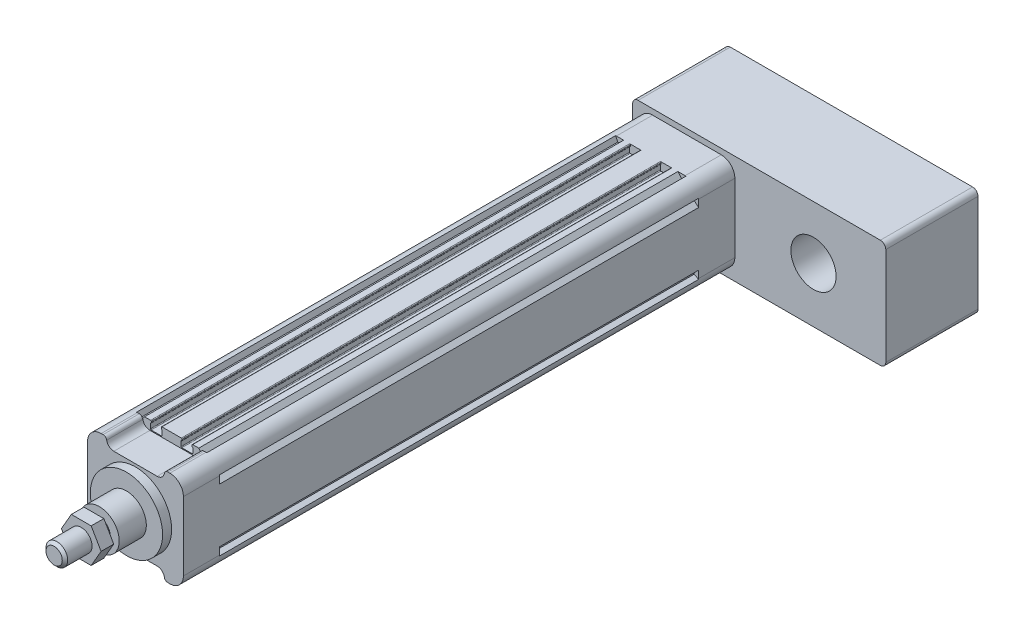
SolidWorks part; units mm, degrees
ref_plane "Front" through (0, 0, 0) normal (0, 0, 1) x (1, 0, 0)
ref_plane "Top" through (0, 0, 0) normal (0, 1, 0) x (1, 0, 0)
ref_plane "Right" through (0, 0, 0) normal (1, 0, 0) x (0, 0, -1)
sketch "草图1" plane through (0, 0, 0) normal (0, 0, 1) x (1, 0, 0)
  line L0 (19.7737, 3) -> (23.3, 3)
  line L1 (23.3, 3) -> (23.3, -3)
  line L2 (23.3, -3) -> (19.7737, -3)
  line L3 (-19.7737, -3) -> (-23.3, -3)
  line L4 (-23.3, -3) -> (-23.3, 3)
  line L5 (-23.3, 3) -> (-19.7737, 3)
  line L6 (-18.2, 24) -> (-19.4434, 26.4869)
  line L7 (-26.4869, 19.4434) -> (-24, 18.2)
  line L8 (-24, 18.2) -> (-24, 17.1)
  line L9 (-24, 17.1) -> (-26.5, 15)
  line L10 (-26.5, 15) -> (-26.5, -15)
  line L11 (-26.5, -15) -> (-24, -17.1)
  line L12 (-24, -17.1) -> (-24, -18.2)
  line L13 (-24, -18.2) -> (-26.4869, -19.4434)
  line L14 (-19.4434, -26.4869) -> (-18.2, -24)
  line L15 (-18.2, -24) -> (-17.1, -24)
  line L16 (-17.1, -24) -> (-15, -26.5)
  line L17 (-15, -26.5) -> (-11.65, -26.5)
  line L18 (-11.25, -26.1) -> (-11.25, -25.6)
  line L19 (-11.65, -25.2) -> (-11.75, -25.2)
  line L20 (-11.75, -25.2) -> (-11.75, -22.4)
  line L21 (-11.35, -22) -> (-5.65, -22)
  line L22 (-5.25, -22.4) -> (-5.25, -25.2)
  line L23 (-5.25, -25.2) -> (-5.35, -25.2)
  line L24 (-5.75, -25.6) -> (-5.75, -26.1)
  line L25 (-5.35, -26.5) -> (5.35, -26.5)
  line L26 (5.75, -26.1) -> (5.75, -25.6)
  line L27 (5.35, -25.2) -> (5.25, -25.2)
  line L28 (5.25, -25.2) -> (5.25, -22.4)
  line L29 (5.65, -22) -> (11.35, -22)
  line L30 (11.75, -22.4) -> (11.75, -25.2)
  line L31 (11.75, -25.2) -> (11.65, -25.2)
  line L32 (11.25, -25.6) -> (11.25, -26.1)
  line L33 (11.65, -26.5) -> (15, -26.5)
  line L34 (15, -26.5) -> (17.1, -24)
  line L35 (17.1, -24) -> (18.2, -24)
  line L36 (18.2, -24) -> (19.4434, -26.4869)
  line L37 (26.4869, -19.4434) -> (24, -18.2)
  line L38 (24, -18.2) -> (24, -17.1)
  line L39 (24, -17.1) -> (26.5, -15)
  line L40 (26.5, -15) -> (26.5, 15)
  line L41 (26.5, 15) -> (24, 17.1)
  line L42 (24, 17.1) -> (24, 18.2)
  line L43 (24, 18.2) -> (26.4869, 19.4434)
  line L44 (19.4434, 26.4869) -> (18.2, 24)
  line L45 (18.2, 24) -> (17.1, 24)
  line L46 (17.1, 24) -> (15, 26.5)
  line L47 (15, 26.5) -> (11.65, 26.5)
  line L48 (11.25, 26.1) -> (11.25, 25.6)
  line L49 (11.65, 25.2) -> (11.75, 25.2)
  line L50 (11.75, 25.2) -> (11.75, 22.4)
  line L51 (11.35, 22) -> (5.65, 22)
  line L52 (5.25, 22.4) -> (5.25, 25.2)
  line L53 (5.25, 25.2) -> (5.35, 25.2)
  line L54 (5.75, 25.6) -> (5.75, 26.1)
  line L55 (5.35, 26.5) -> (-5.35, 26.5)
  line L56 (-5.75, 26.1) -> (-5.75, 25.6)
  line L57 (-5.35, 25.2) -> (-5.25, 25.2)
  line L58 (-5.25, 25.2) -> (-5.25, 22.4)
  line L59 (-5.65, 22) -> (-11.35, 22)
  line L60 (-11.75, 22.4) -> (-11.75, 25.2)
  line L61 (-11.75, 25.2) -> (-11.65, 25.2)
  line L62 (-11.25, 25.6) -> (-11.25, 26.1)
  line L63 (-11.65, 26.5) -> (-15, 26.5)
  line L64 (-15, 26.5) -> (-17.1, 24)
  line L65 (-17.1, 24) -> (-18.2, 24)
  arc A0 (19.7737, 3) -> (-19.7737, 3) centre (0, 0) ccw
  arc A1 (-19.7737, -3) -> (19.7737, -3) centre (0, 0) ccw
  circle A2 centre (19, 19) radius 2.1
  circle A3 centre (19, -19) radius 2.1
  circle A4 centre (-19, -19) radius 2.1
  circle A5 centre (-19, 19) radius 2.1
  arc A6 (-19.4434, 26.4869) -> (-26.4869, 19.4434) centre (-19, 19) ccw
  arc A7 (-26.4869, -19.4434) -> (-19.4434, -26.4869) centre (-19, -19) ccw
  arc A8 (-11.65, -26.5) -> (-11.25, -26.1) centre (-11.65, -26.1) ccw
  arc A9 (-11.25, -25.6) -> (-11.65, -25.2) centre (-11.65, -25.6) ccw
  arc A10 (-11.35, -22) -> (-11.75, -22.4) centre (-11.35, -22.4) ccw
  arc A11 (-5.25, -22.4) -> (-5.65, -22) centre (-5.65, -22.4) ccw
  arc A12 (-5.35, -25.2) -> (-5.75, -25.6) centre (-5.35, -25.6) ccw
  arc A13 (-5.75, -26.1) -> (-5.35, -26.5) centre (-5.35, -26.1) ccw
  arc A14 (5.35, -26.5) -> (5.75, -26.1) centre (5.35, -26.1) ccw
  arc A15 (5.75, -25.6) -> (5.35, -25.2) centre (5.35, -25.6) ccw
  arc A16 (5.65, -22) -> (5.25, -22.4) centre (5.65, -22.4) ccw
  arc A17 (11.75, -22.4) -> (11.35, -22) centre (11.35, -22.4) ccw
  arc A18 (11.65, -25.2) -> (11.25, -25.6) centre (11.65, -25.6) ccw
  arc A19 (11.25, -26.1) -> (11.65, -26.5) centre (11.65, -26.1) ccw
  arc A20 (19.4434, -26.4869) -> (26.4869, -19.4434) centre (19, -19) ccw
  arc A21 (26.4869, 19.4434) -> (19.4434, 26.4869) centre (19, 19) ccw
  arc A22 (11.65, 26.5) -> (11.25, 26.1) centre (11.65, 26.1) ccw
  arc A23 (11.25, 25.6) -> (11.65, 25.2) centre (11.65, 25.6) ccw
  arc A24 (11.35, 22) -> (11.75, 22.4) centre (11.35, 22.4) ccw
  arc A25 (5.25, 22.4) -> (5.65, 22) centre (5.65, 22.4) ccw
  arc A26 (5.35, 25.2) -> (5.75, 25.6) centre (5.35, 25.6) ccw
  arc A27 (5.75, 26.1) -> (5.35, 26.5) centre (5.35, 26.1) ccw
  arc A28 (-5.35, 26.5) -> (-5.75, 26.1) centre (-5.35, 26.1) ccw
  arc A29 (-5.75, 25.6) -> (-5.35, 25.2) centre (-5.35, 25.6) ccw
  arc A30 (-5.65, 22) -> (-5.25, 22.4) centre (-5.65, 22.4) ccw
  arc A31 (-11.75, 22.4) -> (-11.35, 22) centre (-11.35, 22.4) ccw
  arc A32 (-11.65, 25.2) -> (-11.25, 25.6) centre (-11.65, 25.6) ccw
  arc A33 (-11.25, 26.1) -> (-11.65, 26.5) centre (-11.65, 26.1) ccw
extrude "凸台-拉伸1" add sketch "草图1" along normal blind 265
sketch "草图6" plane through (0, 0, 265) normal (0, 0, 1) x (1, 0, 0)
  line L0 (0, 0) -> (19, 0) construction
  line L2 (-26.5, -19) -> (-26.5, 19)
  line L3 (-19, 26.5) -> (-17.9161, 26.5)
  line L4 (26.5, -19) -> (26.5, 19)
  line L5 (-26.5, -26.5) -> (26.5, 26.5) construction
  line L6 (-26.5, 26.5) -> (26.5, -26.5) construction
  line L7 (-12, 21.5) -> (12, 21.5)
  line L9 (19, 26.5) -> (17.9161, 26.5)
  line L10 (19, -26.5) -> (17.9161, -26.5)
  line L11 (-12, -21.5) -> (12, -21.5)
  line L12 (-19, -26.5) -> (-17.9161, -26.5)
  arc A0 (12, 21.5) -> (15.9441, 24.8333) centre (12, 25.5) ccw
  arc A1 (-15.9441, 24.8333) -> (-12, 21.5) centre (-12, 25.5) ccw
  arc A2 (-15.9441, 24.8333) -> (-17.9161, 26.5) centre (-17.9161, 24.5) ccw
  arc A3 (15.9441, 24.8333) -> (17.9161, 26.5) centre (17.9161, 24.5) cw
  arc A4 (-26.5, -19) -> (-19, -26.5) centre (-19, -19) ccw
  arc A5 (19, -26.5) -> (26.5, -19) centre (19, -19) ccw
  arc A6 (26.5, 19) -> (19, 26.5) centre (19, 19) ccw
  arc A7 (-26.5, 19) -> (-19, 26.5) centre (-19, 19) cw
  arc A8 (15.9441, -24.8333) -> (17.9161, -26.5) centre (17.9161, -24.5) ccw
  arc A9 (12, -21.5) -> (15.9441, -24.8333) centre (12, -25.5) cw
  arc A10 (-15.9441, -24.8333) -> (-12, -21.5) centre (-12, -25.5) cw
  arc A11 (-15.9441, -24.8333) -> (-17.9161, -26.5) centre (-17.9161, -24.5) cw
  point P0 (0, 0)
  point P9 (0, 21.5)
  point P13 (20, 20.8461)
  point P16 (-12, 20.8461)
  dimension "D5" = 4
  dimension "D6" = 2
  dimension "D7" = 2
  dimension "D9" = 7.5
  dimension "D1" = 53
  dimension "D2" = 53
  dimension "D3" = 26.5
  dimension "D4" = 24
  dimension "D8" = 5
extrude "凸台-拉伸2" add sketch "草图6" along normal blind 20
sketch "草图7" plane through (0, 0, 285) normal (0, 0, 1) x (1, 0, 0)
  circle A0 centre (0, 0) radius 20
  dimension "D1" = 40
extrude "凸台-拉伸3" add sketch "草图7" along normal blind 5
sketch "草图9" plane through (0, 0, 290) normal (0, 0, 1) x (1, 0, 0)
  circle A0 centre (0, 0) radius 11
  dimension "D1" = 22
extrude "凸台-拉伸4" add sketch "草图9" along normal blind 15
sketch "草图10" plane through (0, 0, 305) normal (0, 0, 1) x (1, 0, 0)
  circle A0 centre (0, 0) radius 6
  dimension "D1" = 12
extrude "凸台-拉伸5" add sketch "草图10" along normal blind 25
sketch "草图11" plane through (0, 0, 0) normal (0, 0, -1) x (-1, 0, 0)
  line L1 (-19, -26.5) -> (19, -26.5)
  line L2 (-26.5, -19) -> (-26.5, 19)
  line L3 (-19, 26.5) -> (19, 26.5)
  line L4 (26.5, -19) -> (26.5, 19)
  line L5 (-26.5, -26.5) -> (26.5, 26.5) construction
  line L6 (-26.5, 26.5) -> (26.5, -26.5) construction
  arc A0 (-26.5, -19) -> (-19, -26.5) centre (-19, -19) ccw
  arc A1 (19, -26.5) -> (26.5, -19) centre (19, -19) ccw
  arc A2 (26.5, 19) -> (19, 26.5) centre (19, 19) ccw
  arc A3 (-26.5, 19) -> (-19, 26.5) centre (-19, 19) cw
  point P0 (0, 0)
  dimension "D3" = 7.5
  dimension "D1" = 53
  dimension "D2" = 53
extrude "凸台-拉伸6" add sketch "草图11" along normal blind 20
sketch "草图12" plane through (0, 0, -20) normal (0, 0, -1) x (-1, 0, 0)
  line L1 (-107, -30.4042) -> (27, -30.4042)
  line L2 (-110, -27.4042) -> (-110, 26.5958)
  line L3 (-107, 29.5958) -> (27, 29.5958)
  line L4 (30, -27.4042) -> (30, 26.5958)
  line L5 (-110, -30.4042) -> (30, 29.5958) construction
  line L6 (-110, 29.5958) -> (30, -30.4042) construction
  arc A0 (27, 29.5958) -> (30, 26.5958) centre (27, 26.5958) cw
  arc A1 (30, -27.4042) -> (27, -30.4042) centre (27, -27.4042) cw
  arc A2 (-110, -27.4042) -> (-107, -30.4042) centre (-107, -27.4042) ccw
  arc A3 (-110, 26.5958) -> (-107, 29.5958) centre (-107, 26.5958) cw
  point P0 (-40, -0.4042)
  dimension "D4" = 3
  dimension "D1" = 60
  dimension "D2" = 140
  dimension "D3" = 30
extrude "凸台-拉伸7" add sketch "草图12" along normal blind 51
sketch "草图13" plane through (0, 0, -20) normal (0, 0, 1) x (1, 0, 0)
  circle A0 centre (70, 0) radius 12.5
  dimension "D2" = 25
  dimension "D1" = 70
extrude "切除-拉伸2" cut sketch "草图13" against normal blind 30
hole_wizard "M6 螺纹孔1" positions "草图14" profile "草图15" tap size "M6" standard "GB"
sketch "草图14" plane through (0, 0, -71) normal (0, 0, -1) x (-1, 0, 0)
  line L0 (30, -27.4042) -> (30, 26.5958) construction
  point P0 (19, -19)
  dimension "D1" = 11
  dimension "D2" = 19
sketch "草图15" plane through (-19, -19, -71) normal (1, 0, 0) x (0, 1, 0)
  line L0 (0, 0) -> (0, 16.5022)
  line L1 (0, 16.5022) -> (2.5, 15)
  line L2 (2.5, 15) -> (2.5, 0)
  line L5 (2.5, 0) -> (0, 0)
  line L10 (0, 16.5022) -> (-2.5, 15) construction
  line L11 (0, -6.35) -> (0, 107.95) construction
  dimension "螺纹孔钻头直径" = 5
  dimension "螺纹孔钻头深度" = 15
  dimension "导头角度" = 118
cosmetic thread "孔螺蚊线4" parameters "D1"=12, "D2"=6
pattern_linear "阵列(线性)1" count 2 spacing 38 along (0, 1, 0) count 2 spacing 38 along (1, 0, 0) of "M6 螺纹孔1"
hole_wizard "M6 螺纹孔2" positions "草图16" profile "草图17" tap size "M6" standard "GB"
sketch "草图16" plane through (0, 0, -71) normal (0, 0, -1) x (-1, 0, 0)
  circle A1 centre (-19, 19) radius 2.5 construction
  circle A2 centre (-19, -19) radius 2.5 construction
  point P0 (-84, -19)
  point P2 (-84, 19)
  dimension "D3" = 65
  dimension "D1" = 19
  dimension "D2" = 19
  dimension "D4" = 65
sketch "草图17" plane through (84, -19, -71) normal (1, 0, 0) x (0, 1, 0)
  line L0 (0, 0) -> (0, 16.5022)
  line L1 (0, 16.5022) -> (2.5, 15)
  line L2 (2.5, 15) -> (2.5, 0)
  line L5 (2.5, 0) -> (0, 0)
  line L10 (0, 16.5022) -> (-2.5, 15) construction
  line L11 (0, -6.35) -> (0, 107.95) construction
  dimension "螺纹孔钻头直径" = 5
  dimension "螺纹孔钻头深度" = 15
  dimension "导头角度" = 118
cosmetic thread "孔螺蚊线5" parameters "D1"=12, "D2"=6
cosmetic thread "孔螺蚊线6" parameters "D1"=12, "D2"=6
hole_wizard "M6 螺纹孔3" positions "草图19" profile "草图20" tap size "M6" standard "GB"
sketch "草图19" plane through (-26.5, 0, 0) normal (-1, 0, 0) x (0, 0, 1)
  line L0 (285, 19) -> (285, -19) construction
  point P0 (275, 11)
  point P2 (275, -11)
  dimension "D1" = 10
  dimension "D2" = 10
  dimension "D3" = 22
  dimension "D4" = 11
sketch "草图20" plane through (-26.5, 11, 275) normal (0, 1, 0) x (0, 0, 1)
  line L0 (0, 0) -> (0, 16.5022)
  line L1 (0, 16.5022) -> (2.5, 15)
  line L2 (2.5, 15) -> (2.5, 0)
  line L5 (2.5, 0) -> (0, 0)
  line L10 (0, 16.5022) -> (-2.5, 15) construction
  line L11 (0, -6.35) -> (0, 107.95) construction
  dimension "螺纹孔钻头直径" = 5
  dimension "螺纹孔钻头深度" = 15
  dimension "导头角度" = 118
cosmetic thread "孔螺蚊线7" parameters "D1"=12, "D2"=6
cosmetic thread "孔螺蚊线8" parameters "D1"=12, "D2"=6
hole_wizard "M6 螺纹孔4" positions "草图21" profile "草图22" tap size "M6" standard "GB"
sketch "草图21" plane through (-26.5, 0, 0) normal (-1, 0, 0) x (0, 0, 1)
  line L0 (-20, -27.4042) -> (-20, 26.5958) construction
  line L1 (-20, -19) -> (-20, 19) construction
  point P0 (-10, 11)
  point P2 (-10, -11)
  dimension "D1" = 10
  dimension "D2" = 10
  dimension "D3" = 11
  dimension "D4" = 11
sketch "草图22" plane through (-26.5, 11, -10) normal (0, 1, 0) x (0, 0, 1)
  line L0 (0, 0) -> (0, 16.5022)
  line L1 (0, 16.5022) -> (2.5, 15)
  line L2 (2.5, 15) -> (2.5, 0)
  line L5 (2.5, 0) -> (0, 0)
  line L10 (0, 16.5022) -> (-2.5, 15) construction
  line L11 (0, -6.35) -> (0, 107.95) construction
  dimension "螺纹孔钻头直径" = 5
  dimension "螺纹孔钻头深度" = 15
  dimension "导头角度" = 118
cosmetic thread "孔螺蚊线9" parameters "D1"=12, "D2"=6
cosmetic thread "孔螺蚊线10" parameters "D1"=12, "D2"=6
chamfer "倒角1" distance 1.5 angle 45 1 edges at (6, 0, 330)
sketch "草图23" plane through (0, 0, 305) normal (0, 0, 1) x (1, 0, 0)
  line L1 (10.9697, 0) -> (5.4848, 9.5)
  line L2 (5.4848, 9.5) -> (-5.4848, 9.5)
  line L3 (-5.4848, 9.5) -> (-10.9697, 0)
  line L4 (-10.9697, 0) -> (-5.4848, -9.5)
  line L5 (-5.4848, -9.5) -> (5.4848, -9.5)
  line L6 (5.4848, -9.5) -> (10.9697, 0)
  circle A0 centre (0, 0) radius 9.5 construction
  dimension "D1" = 19
extrude "凸台-拉伸8" add sketch "草图23" along normal blind 7 from offset 3
